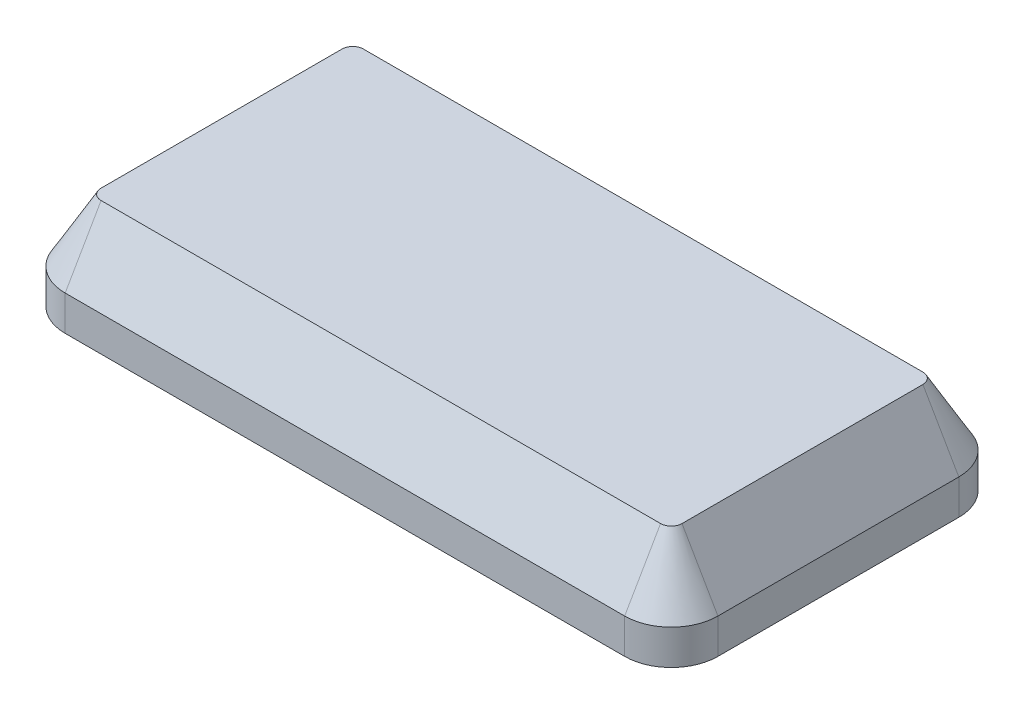
SolidWorks part; units mm, degrees
material "ABS"
ref_plane "前视基准面" through (0, 0, 0) normal (0, 0, 1) x (1, 0, 0)
ref_plane "上视基准面" through (0, 0, 0) normal (0, 1, 0) x (1, 0, 0)
ref_plane "右视基准面" through (0, 0, 0) normal (1, 0, 0) x (0, 0, -1)
sketch "草图1" plane through (0, 0, 0) normal (0, 1, 0) x (1, 0, 0)
  line L1 (-36, 21.5) -> (36, 21.5)
  line L2 (-42, 15.5) -> (-42, -15.5)
  line L3 (-36, -21.5) -> (36, -21.5)
  line L4 (42, 15.5) -> (42, -15.5)
  line L5 (-42, 21.5) -> (42, -21.5) construction
  line L6 (-42, -21.5) -> (42, 21.5) construction
  arc A0 (36, -21.5) -> (42, -15.5) centre (36, -15.5) ccw
  arc A1 (-42, -15.5) -> (-36, -21.5) centre (-36, -15.5) ccw
  arc A2 (36, 21.5) -> (42, 15.5) centre (36, 15.5) cw
  arc A3 (-36, 21.5) -> (-42, 15.5) centre (-36, 15.5) ccw
  point P0 (0, 0)
  dimension "D3" = 6
  dimension "D1" = 84
  dimension "D2" = 43
extrude "凸台-拉伸1" add sketch "草图1" along normal blind 4.5
sketch "草图2" plane through (0, 0, 0) normal (0, -1, 0) x (1, 0, 0)
  line L8 (36, 20.5) -> (-36, 20.5)
  line L9 (-41, 15.5) -> (-41, -15.5)
  line L10 (-36, -20.5) -> (36, -20.5)
  line L11 (41, -15.5) -> (41, 15.5)
  line L12 (36, 20.5) -> (-36, 20.5)
  line L13 (-41, 15.5) -> (-41, -15.5)
  line L14 (-36, -20.5) -> (36, -20.5)
  line L15 (41, -15.5) -> (41, 15.5)
  arc A8 (41, 15.5) -> (36, 20.5) centre (36, 15.5) ccw
  arc A9 (-36, 20.5) -> (-41, 15.5) centre (-36, 15.5) ccw
  arc A10 (-41, -15.5) -> (-36, -20.5) centre (-36, -15.5) ccw
  arc A11 (36, -20.5) -> (41, -15.5) centre (36, -15.5) ccw
  arc A12 (41, 15.5) -> (36, 20.5) centre (36, 15.5) ccw
  arc A13 (-36, 20.5) -> (-41, 15.5) centre (-36, 15.5) ccw
  arc A14 (-41, -15.5) -> (-36, -20.5) centre (-36, -15.5) ccw
  arc A15 (36, -20.5) -> (41, -15.5) centre (36, -15.5) ccw
  dimension "D1" = 1
extrude "切除-拉伸1" cut sketch "草图2" against normal blind 1
sketch "草图3" plane through (0, 1, 0) normal (0, -1, 0) x (-1, 0, 0)
  line L0 (0, 0) -> (0, -18.2209) construction
  line L1 (0, 0) -> (28.1035, 0) construction
  line L6 (-36, -20.5) -> (36, -20.5)
  line L7 (41, -15.5) -> (41, 15.5)
  line L8 (36, 20.5) -> (-36, 20.5)
  line L9 (-41, 15.5) -> (-41, -15.5)
  line L10 (-36, -20.5) -> (36, -20.5)
  line L11 (41, -15.5) -> (41, 15.5)
  line L12 (36, 20.5) -> (-36, 20.5)
  line L13 (-41, 15.5) -> (-41, -15.5)
  circle A0 centre (36, -15.5) radius 2.5
  circle A1 centre (36, 15.5) radius 2.5
  circle A2 centre (-36, 15.5) radius 2.5
  circle A3 centre (-36, -15.5) radius 2.5
  circle A4 centre (36, -15.5) radius 1.65
  circle A5 centre (36, 15.5) radius 1.65
  circle A6 centre (-36, -15.5) radius 1.65
  circle A7 centre (-36, 15.5) radius 1.65
  arc A12 (-41, -15.5) -> (-36, -20.5) centre (-36, -15.5) ccw
  arc A13 (36, -20.5) -> (41, -15.5) centre (36, -15.5) ccw
  arc A14 (41, 15.5) -> (36, 20.5) centre (36, 15.5) ccw
  arc A15 (-36, 20.5) -> (-41, 15.5) centre (-36, 15.5) ccw
  arc A16 (-41, -15.5) -> (-36, -20.5) centre (-36, -15.5) ccw
  arc A17 (36, -20.5) -> (41, -15.5) centre (36, -15.5) ccw
  arc A18 (41, 15.5) -> (36, 20.5) centre (36, 15.5) ccw
  arc A19 (-36, 20.5) -> (-41, 15.5) centre (-36, 15.5) ccw
  arc M11 (-41, -15.5) -> (-36, -20.5) centre (-36, -15.5) ccw
  line M12 (-36, -20.5) -> (36, -20.5)
  arc M13 (36, -20.5) -> (41, -15.5) centre (36, -15.5) ccw
  line M14 (41, -15.5) -> (41, 15.5)
  arc M15 (41, 15.5) -> (36, 20.5) centre (36, 15.5) ccw
  line M16 (36, 20.5) -> (-36, 20.5)
  arc M17 (-36, 20.5) -> (-41, 15.5) centre (-36, 15.5) ccw
  line M18 (-41, 15.5) -> (-41, -15.5)
  dimension "D1" = 5
  dimension "D2" = 3.3
  dimension "D3" = 0
extrude "切除-拉伸2" cut sketch "草图3" against normal blind 3.4 contours A1 A0 A2 A3 M18 M11 M12 M13 M14 M15 M16 M17 | A5 | A4 | A6 | A7
sketch "草图5" plane through (0, 4.5, 0) normal (0, 1, 0) x (1, 0, 0)
  line L4 (42, -15.5) -> (42, 15.5)
  line L5 (36, 21.5) -> (-36, 21.5)
  line L6 (-42, 15.5) -> (-42, -15.5)
  line L7 (-36, -21.5) -> (36, -21.5)
  line L8 (42, -15.5) -> (42, 15.5)
  line L9 (36, 21.5) -> (-36, 21.5)
  line L10 (-42, 15.5) -> (-42, -15.5)
  line L11 (-36, -21.5) -> (36, -21.5)
  arc A4 (36, -21.5) -> (42, -15.5) centre (36, -15.5) ccw
  arc A5 (42, 15.5) -> (36, 21.5) centre (36, 15.5) ccw
  arc A6 (-36, 21.5) -> (-42, 15.5) centre (-36, 15.5) ccw
  arc A7 (-42, -15.5) -> (-36, -21.5) centre (-36, -15.5) ccw
  arc A8 (36, -21.5) -> (42, -15.5) centre (36, -15.5) ccw
  arc A9 (42, 15.5) -> (36, 21.5) centre (36, 15.5) ccw
  arc A10 (-36, 21.5) -> (-42, 15.5) centre (-36, 15.5) ccw
  arc A11 (-42, -15.5) -> (-36, -21.5) centre (-36, -15.5) ccw
  dimension "D1" = 0
extrude "凸台-拉伸2" add sketch "草图5" along normal blind 8 draft 30
